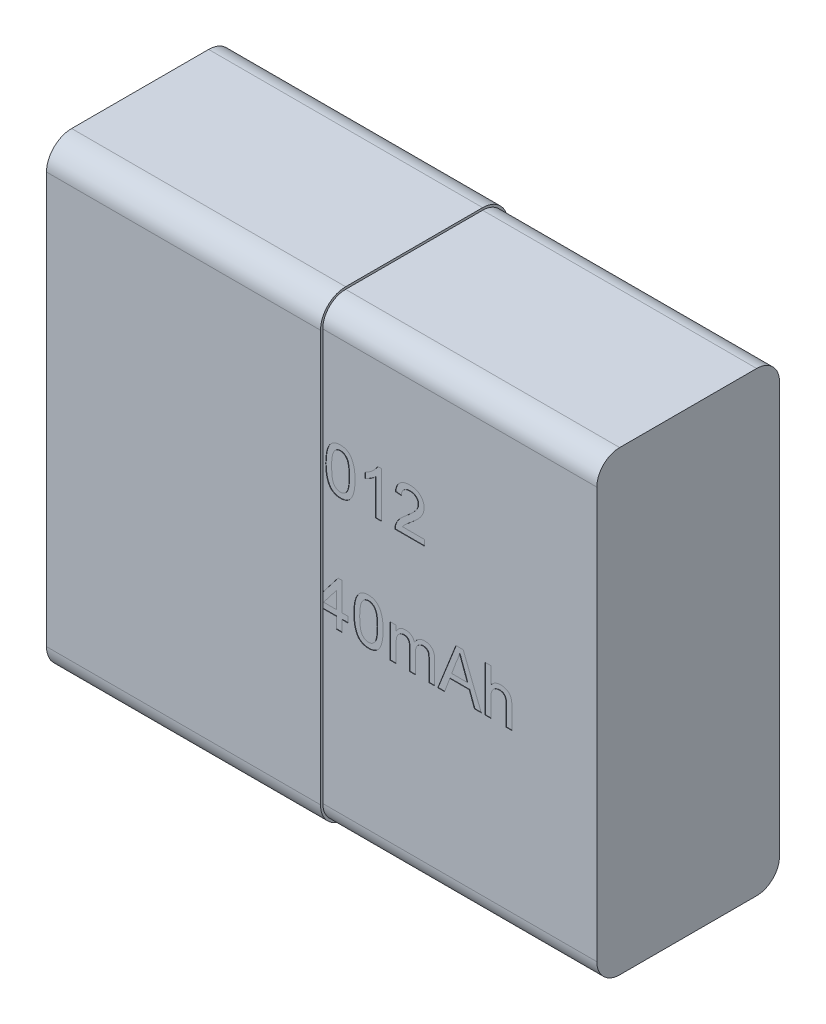
SolidWorks part; units mm, degrees
ref_plane "Plan de face" through (0, 0, 0) normal (0, 0, 1) x (1, 0, 0)
ref_plane "Plan de dessus" through (0, 0, 0) normal (0, 1, 0) x (1, 0, 0)
ref_plane "Plan de droite" through (0, 0, 0) normal (1, 0, 0) x (0, 0, -1)
sketch "Sketch1" plane through (0, 0, 0) normal (0, 0, 1) x (1, 0, 0)
  line L1 (6, -5) -> (-6, -5)
  line L2 (6, -5) -> (6, 5)
  line L3 (6, 5) -> (-6, 5)
  line L4 (-6, -5) -> (-6, 5)
  line L5 (6, -5) -> (-6, 5) construction
  line L6 (6, 5) -> (-6, -5) construction
  point P0 (0, 0)
  dimension "D1" = 10
  dimension "D2" = 12
extrude "Boss-Extrude1" add sketch "Sketch1" along normal blind 4
fillet "Fillet1" radius 0.5 4 edges at (0, -5, 0) (0, -5, 4) (0, 5, 4) (0, 5, 0)
sketch "Sketch2" plane through (-6, 0, 0) normal (-1, 0, 0) x (0, 0, 1)
  line L4 (0, 4.5) -> (0, -4.5) construction
  line L5 (3.5, -5) -> (0.5, -5) construction
  line L6 (4, 4.5) -> (4, -4.5) construction
  line L7 (3.5, 5) -> (0.5, 5) construction
  line L8 (0.5, -5.05) -> (3.5, -5.05)
  line L9 (-0.05, 4.5) -> (-0.05, -4.5)
  line L10 (3.5, 5.05) -> (0.5, 5.05)
  line L11 (4.05, -4.5) -> (4.05, 4.5)
  line L12 (0.5, -5.05) -> (3.5, -5.05)
  line L13 (-0.05, 4.5) -> (-0.05, -4.5)
  line L14 (3.5, 5.05) -> (0.5, 5.05)
  line L15 (4.05, -4.5) -> (4.05, 4.5)
  line L16 (0, 4.5) -> (0, -4.5)
  line L17 (3.5, -5) -> (0.5, -5)
  line L18 (4, 4.5) -> (4, -4.5)
  line L19 (3.5, 5) -> (0.5, 5)
  arc A4 (0.5, 5) -> (0, 4.5) centre (0.5, 4.5) ccw construction
  arc A5 (0, -4.5) -> (0.5, -5) centre (0.5, -4.5) ccw construction
  arc A6 (3.5, -5) -> (4, -4.5) centre (3.5, -4.5) ccw construction
  arc A7 (4, 4.5) -> (3.5, 5) centre (3.5, 4.5) ccw construction
  arc A8 (3.5, -5.05) -> (4.05, -4.5) centre (3.5, -4.5) ccw
  arc A9 (-0.05, -4.5) -> (0.5, -5.05) centre (0.5, -4.5) ccw
  arc A10 (0.5, 5.05) -> (-0.05, 4.5) centre (0.5, 4.5) ccw
  arc A11 (4.05, 4.5) -> (3.5, 5.05) centre (3.5, 4.5) ccw
  arc A12 (3.5, -5.05) -> (4.05, -4.5) centre (3.5, -4.5) ccw
  arc A13 (-0.05, -4.5) -> (0.5, -5.05) centre (0.5, -4.5) ccw
  arc A14 (0.5, 5.05) -> (-0.05, 4.5) centre (0.5, 4.5) ccw
  arc A15 (4.05, 4.5) -> (3.5, 5.05) centre (3.5, 4.5) ccw
  arc A16 (0.5, 5) -> (0, 4.5) centre (0.5, 4.5) ccw
  arc A17 (0, -4.5) -> (0.5, -5) centre (0.5, -4.5) ccw
  arc A18 (3.5, -5) -> (4, -4.5) centre (3.5, -4.5) ccw
  arc A19 (4, 4.5) -> (3.5, 5) centre (3.5, 4.5) ccw
  dimension "D1" = 0.05
extrude "Boss-Extrude2" add sketch "Sketch2" against normal blind 6 separate body
sketch "Sketch5" plane through (0, 0, 4) normal (0, 0, 1) x (1, 0, 0)
  line L1 (-7.9429, -2.5072) -> (7.9429, -2.5072) construction
  line L2 (-7.9429, -2.5072) -> (-7.9429, 1.4928) construction
  line L3 (-7.9429, 1.4928) -> (7.9429, 1.4928) construction
  line L4 (7.9429, -2.5072) -> (7.9429, 1.4928) construction
  line L5 (-7.9429, -2.5072) -> (7.9429, 1.4928) construction
  line L6 (-7.9429, 1.4928) -> (7.9429, -2.5072) construction
  text T0 "301012\r\n3.7V - 40mAh" font "Arial" height 1
  point P0 (0, -2.4229)
  point P6 (0, 0)
  point P8 (0, -0.5072)
  dimension "D1" = 4
extrude "Cut-Extrude1" cut sketch "Sketch5" against normal blind 0.01
